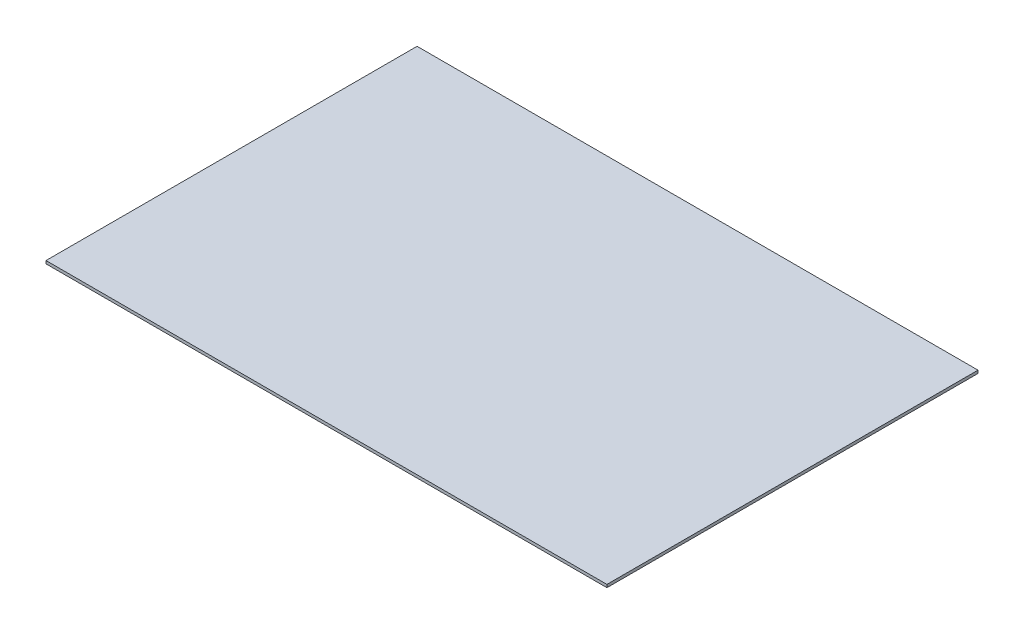
SolidWorks part; units mm, degrees
ref_plane "Front Plane" through (0, 0, 0) normal (0, 0, 1) x (1, 0, 0)
ref_plane "Top Plane" through (0, 0, 0) normal (0, 1, 0) x (1, 0, 0)
ref_plane "Right Plane" through (0, 0, 0) normal (1, 0, 0) x (0, 0, -1)
sketch "Sketch1" plane through (0, 0, 0) normal (0, 1, 0) x (1, 0, 0)
  line L1 (-195, 130.5) -> (195, 130.5)
  line L2 (-195, 130.5) -> (-195, -127.5)
  line L3 (-195, -127.5) -> (195, -127.5)
  line L4 (195, 130.5) -> (195, -127.5)
extrude "Boss-Extrude1" add sketch "Sketch1" along normal blind 2
